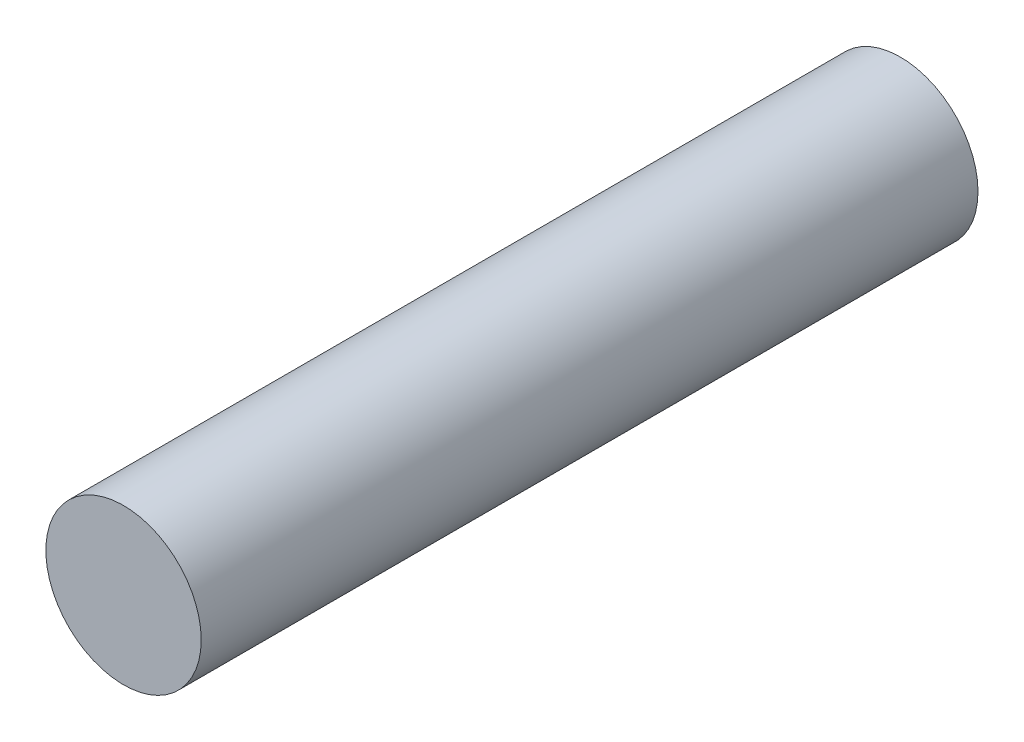
SolidWorks part; units mm, degrees
ref_plane "前视基准面" through (0, 0, 0) normal (0, 0, 1) x (1, 0, 0)
ref_plane "上视基准面" through (0, 0, 0) normal (0, 1, 0) x (1, 0, 0)
ref_plane "右视基准面" through (0, 0, 0) normal (1, 0, 0) x (0, 0, -1)
sketch "草图1" plane through (0, 0, 0) normal (0, 0, 1) x (1, 0, 0)
  circle A0 centre (11.2034, 3.2991) radius 1
extrude "凸台-拉伸1" add sketch "草图1" along normal blind 10
